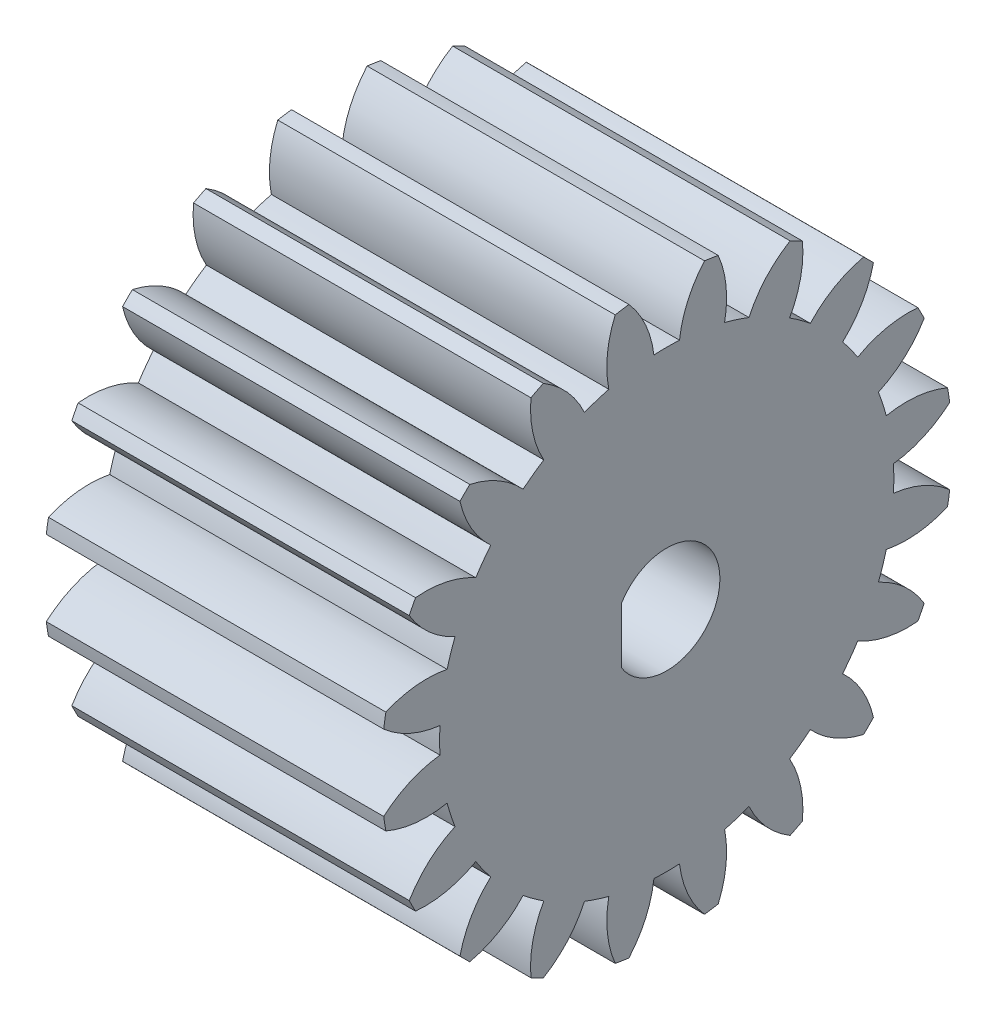
SolidWorks part; units mm, degrees
ref_plane "Plane1" through (0, 0, 0) normal (0, 0, 1) x (1, 0, 0)
ref_plane "Plane2" through (0, 0, 0) normal (0, 1, 0) x (1, 0, 0)
ref_plane "Plane3" through (0, 0, 0) normal (1, 0, 0) x (0, 0, -1)
other "Configuration Table"
sketch "HoldingSke" plane through (0, 0, 0) normal (0, 1, 0) x (1, 0, 0)
  line L0 (0, 0) -> (0.4698, -0.171)
  line L1 (-15, 0) -> (100, 0) construction
  line L2 (0, 0) -> (-2.1039, 2.3779)
  line L3 (0, 0) -> (-11.863, 4.5341)
  line L4 (0, 0) -> (8.1152, 2.9537)
  line L5 (0, 0) -> (-46.8476, -17.4728)
  line L6 (0, 0) -> (-21.553, -14.5419)
  line L7 (-2.1039, 2.3779) -> (8.6586, 51.2059)
  line L8 (-76.2, 54.61) -> (-75.9, 54.61)
  line L9 (-71.009, 38.7566) -> (-53.1078, 45.2721)
  line L10 (-76.2, 71.12) -> (104.1128, 71.12)
  line L11 (0, 0) -> (-26, 0)
  line L12 (-76.2, 101.6) -> (-76.133, 101.6)
  line L13 (24.9733, 27.94) -> (52.9518, 28.4284)
  line L14 (24.9733, 27.94) -> (24.9743, 27.94)
  line L15 (24.9733, 27.94) -> (100.4006, 29.5858)
  line L16 (-63.627, -2) -> (-12.827, -2)
  circle A0 centre (0, 0) radius 1
  circle A1 centre (0, 0) radius 17.499
  circle A2 centre (0, 0) radius 37.5
  circle A3 centre (0, 0) radius 1
  dimension "MHD" = 34.998
  dimension "Hub_dia" = 75
  dimension "Bore" = 2
  dimension "MBD" = 2
  dimension "Num_teeth" = 20
  dimension "Pitch" = 0.5
  dimension "Overall_len" = 50
  dimension "Show_teeth" = 20
  dimension "Thickness" = 26
  dimension "OAL" = 50.0001
  dimension "T_dim" = 0.3
  dimension "Ap" = 20
  dimension "H" = 19.05
  dimension "Pitch_radius" = 180.3128
  dimension "Width" = 26
  dimension "Backlash" = 0.067
  dimension "Addendum_fac" = 1
  dimension "Dedendum_fac" = 1.25
  dimension "Clearance_fac" = 0.25
  dimension "Dedendum_add" = 0.001
  dimension "Module" = 2
sketch "BasProSke" plane through (0, 0, 0) normal (0, 1, 0) x (1, 0, 0)
  line L0 (-10, 0) -> (60, 0) construction
  line L1 (0, 0) -> (0, 22)
  line L2 (0, 0) -> (26, 0)
  line L3 (26, 0) -> (26, 22)
  line L4 (26, 22) -> (0, 22)
  dimension "Thickness" = 26
  dimension "Diameter" = 44
revolve "Base-Revolve" add sketch "BasProSke" angle 360 about L0
sketch "TooCutSke" plane through (0, 0, 0) normal (1, 0, 0) x (0, 0, -1)
  line L1 (0, 0) -> (0, 107) construction
  line L2 (0, 0) -> (-1.6864, 19.9288) construction
  line L3 (0, 0) -> (-6.2409, 39.4033) construction
  line L4 (-1.6864, 19.9288) -> (-3.1204, 19.7016) construction
  arc A0 (0.9862, 17.4712) -> (-0.9862, 17.4712) centre (0, 0) ccw
  arc A1 (2.9329, 21.8293) -> (-2.9329, 21.8293) centre (0, 0) ccw
  circle A2 centre (0, 0) radius 20 construction
  circle A3 centre (0, 0) radius 18.7939 construction
  arc A4 (-0.9862, 17.4712) -> (-2.9329, 21.8293) centre (-8.9313, 16.536) ccw
  arc A5 (2.9329, 21.8293) -> (0.9862, 17.4712) centre (8.9313, 16.536) ccw
  dimension "Root_dia" = 34.998
  dimension "Overcut_dia" = 44.0508
  dimension "Pitch_dia" = 40
  dimension "Base_dia" = 37.5877
  dimension "Flank_rad" = 8
  dimension "Half_ang" = 9
  dimension "Half_CT" = 1.4519
extrude "ToothCut" cut sketch "TooCutSke" along normal through all
fillet "Breaks" [suppressed] radius 0.04
fillet "RootFillets" [suppressed] radius 0.501
pattern_circular "TeethCuts" count 20 every 18 about axis through (-10, 0, 0) along (1, 0, 0) of "ToothCut", "RootFillets", "Breaks"
sketch "HubNeaOneSke" plane through (0, 0, 0) normal (-1, 0, 0) x (0, 0, 1)
  circle A0 centre (0, 0) radius 17.499
  dimension "Diameter" = 34.998
extrude "HubNearOne" [suppressed] add sketch "HubNeaOneSke" along normal blind 24.0001
sketch "HubNeaBotSke" plane through (0, 0, 0) normal (-1, 0, 0) x (0, 0, 1)
  circle A0 centre (0, 0) radius 17.499
  dimension "Diameter" = 34.998
extrude "HubNearBoth" [suppressed] add sketch "HubNeaBotSke" along normal blind 12
ref_plane "FarPln" through (26, 0, 0) normal (1, 0, 0) x (0, 0, -1)
sketch "HubFarSke" plane through (26, 0, 0) normal (1, 0, 0) x (0, 0, -1)
  circle A0 centre (0, 0) radius 17.499
  dimension "Diameter" = 34.998
extrude "HubFar" [suppressed] add sketch "HubFarSke" along normal blind 12
sketch "BorSke" plane through (0, 0, 0) normal (1, 0, 0) x (0, 0, -1)
  line L0 (-3.5, -2.1354) -> (-3.5, 2.1354)
  arc A0 (-3.5, -2.1354) -> (-3.5, 2.1354) centre (0, 0) ccw
  dimension "D1" = 8.2
  dimension "D2" = 3.5
extrude "Bore" cut sketch "BorSke" along normal mid plane 100.0001
sketch "KeySke" plane through (0, 0, 0) normal (1, 0, 0) x (0, 0, -1)
  line L0 (-0.4, 0) -> (-0.4, 1.3)
  line L1 (-0.4, 1.3) -> (0.4, 1.3)
  line L2 (0.4, 1.3) -> (0.4, 0)
  line L3 (0, 0) -> (0, 34) construction
  line L4 (-0.4, 0) -> (0.4, 0)
  dimension "Offset" = 1.3
  dimension "Width" = 0.8
extrude "Keyway" [suppressed] cut sketch "KeySke" along normal mid plane 100.0001
pattern_circular "Keyway2" [suppressed] count 2 every 90 about axis through (-10, 0, 0) along (1, 0, 0)
equation "' \"Module@HoldingSke\" = 6.35"
equation "' \"Num_teeth@HoldingSke\" = 12"
equation "' \"Ap@HoldingSke\" =  20"
equation "' \"Ap@HoldingSke\" = 20"
equation "' \"Width@HoldingSke\" = 0.5 * 25.4"
equation "' \"Hub_dia@HoldingSke\"= 1 * 25.4"
equation "' \"Hub_dia@HoldingSke\" = 1 * 25.4"
equation "' \"Overall_len@HoldingSke\" = 1.0 * 25.4"
equation "' \"Bore@HoldingSke\" = 0.75 * 25.4"
equation "' \"T_dim@HoldingSke\" = 0.1 * 25.4"
equation "' \"Width@KeySke\" = 0.25 * 25.4"
equation "' \"Show_teeth@HoldingSke\" = 13"
equation "' \"Backlash@HoldingSke\" = 0.009 * 25.4"
equation "' \"Addendum_fac@HoldingSke\" = 1.0"
equation "' \"Dedendum_fac@HoldingSke\" = 1.25"
equation "' \"Dedendum_add@HoldingSke\" = 0.00005 * 25.4"
equation "' \"Clearance_fac@HoldingSke\" = 0.25"
equation "\"Pitch@HoldingSke\" = 1 / \"Module@HoldingSke\""
equation "\"Overcut_dia@TooCutSke\" = (\"Num_teeth@HoldingSke\" + 2 * \"Addendum_fac@HoldingSke\") / \"Pitch@HoldingSke\" + 0.002 * 25.4"
equation "\"Pitch_dia@TooCutSke\" = \"Num_teeth@HoldingSke\" / \"Pitch@HoldingSke\""
equation "\"Base_dia@TooCutSke\" = \"Num_teeth@HoldingSke\" / \"Pitch@HoldingSke\" * cos((\"Ap@HoldingSke\"  * 3.14159265 / 180))"
equation "\"Root_dia@TooCutSke\" = (\"Num_teeth@HoldingSke\" + 2) / \"Pitch@HoldingSke\" - 2 * (\"Addendum_fac@HoldingSke\" + \"Dedendum_fac@HoldingSke\") / \"Pitch@HoldingSke\" - \"Dedendum_add@HoldingSke\" * 2"
equation "\"Half_ang@TooCutSke\" = 180 / \"Num_teeth@HoldingSke\""
equation "\"Half_CT@TooCutSke\" = \"Num_teeth@HoldingSke\" / \"Pitch@HoldingSke\" * sin((3.14159265 / 2 / \"Num_teeth@HoldingSke\")) / 2 - 7 * \"Backlash@HoldingSke\" / 4"
equation "\"Flank_rad@TooCutSke\" = \"Num_teeth@HoldingSke\" / \"Pitch@HoldingSke\" / 5"
equation "\"Radius@RootFillets\" = \"Clearance_fac@HoldingSke\" / \"Pitch@HoldingSke\" + \"Dedendum_add@HoldingSke\""
equation "\"Break_rad@Breaks\" = 0.02 / \"Pitch@HoldingSke\""
equation "\"Thickness@HoldingSke\" = \"Width@HoldingSke\""
equation "\"OAL@HoldingSke\" = \"Thickness@HoldingSke\""
equation "\"MHD@HoldingSke\" = (\"Num_teeth@HoldingSke\" + 2) / \"Pitch@HoldingSke\" - 2 * (\"Addendum_fac@HoldingSke\" + \"Dedendum_fac@HoldingSke\")  / \"Pitch@HoldingSke\" - \"Dedendum_add@HoldingSke\" * 2"
equation "\"MBD@HoldingSke\" = (\"Num_teeth@HoldingSke\" + 2) / \"Pitch@HoldingSke\" - 2 * (\"Addendum_fac@HoldingSke\" + \"Dedendum_fac@HoldingSke\")  / \"Pitch@HoldingSke\" - \"Dedendum_add@HoldingSke\" * 2 - 0.002 * 25.4"
equation "\"MHD@HoldingSke\" = ((sgn( \"MHD@HoldingSke\" - \"Hub_dia@HoldingSke\" )-1)*( \"MHD@HoldingSke\" - \"Hub_dia@HoldingSke\" ))/-2+ \"Hub_dia@HoldingSke\""
equation "\"MBD@HoldingSke\" = ((sgn( \"MBD@HoldingSke\" - \"Bore@HoldingSke\" )-1)*( \"MBD@HoldingSke\" - \"Bore@HoldingSke\" ))/-2+ \"Bore@HoldingSke\""
equation "\"OAL@HoldingSke\" = ((sgn( \"OAL@HoldingSke\" - \"Overall_len@HoldingSke\" )+1)*( \"OAL@HoldingSke\" - \"Overall_len@HoldingSke\" ))/2 + \"Overall_len@HoldingSke\" + 0.000002 * 25.4"
equation "\"Num_teeth@TeethCuts\" = int( \"Show_teeth@HoldingSke\" ) + 1"
equation "\"Num_teeth@TeethCuts\" = ((sgn( \"Num_teeth@TeethCuts\" - \"Num_teeth@HoldingSke\" )-1)*( \"Num_teeth@TeethCuts\" - \"Num_teeth@HoldingSke\" ))/-2+ \"Num_teeth@HoldingSke\""
equation "\"Num_teeth@TeethCuts\" = ((sgn( \"Num_teeth@TeethCuts\" - 2.0)+1)*( \"Num_teeth@TeethCuts\" - 2.0))/2 +2.0"
equation "\"Angle@TeethCuts\" = 360.0 / \"Num_teeth@HoldingSke\""
equation "\"Diameter@BasProSke\" = (\"Num_teeth@HoldingSke\" + 2 * \"Addendum_fac@HoldingSke\") / \"Pitch@HoldingSke\""
equation "\"Thickness@BasProSke\"  = \"Thickness@HoldingSke\""
equation "' \"Fillet_rad@BasProSke\" =  \"Thickness@HoldingSke\" * 0.05"
equation "' \"Fillet_rad@BasProSke\" = \"Thickness@HoldingSke\" * 0.05"
equation "\"MHD@HoldingSke\" = ((sgn( \"MHD@HoldingSke\" - \"Root_dia@TooCutSke\" )-1)*( \"MHD@HoldingSke\" - \"Root_dia@TooCutSke\" ))/-2+ \"Root_dia@TooCutSke\""
equation "\"Diameter@HubNeaOneSke\" = \"MHD@HoldingSke\""
equation "\"Length@HubNearOne\" = \"OAL@HoldingSke\" - \"Thickness@BasProSke\""
equation "\"Diameter@HubNeaBotSke\" = \"MHD@HoldingSke\""
equation "\"Length@HubNearBoth\" = ( \"OAL@HoldingSke\" - \"Thickness@BasProSke\" ) / 2.0"
equation "\"Thickness@FarPln\" = \"Thickness@BasProSke\""
equation "\"Diameter@HubFarSke\" = \"MHD@HoldingSke\""
equation "\"Length@HubFar\" = ( \"OAL@HoldingSke\" - \"Thickness@BasProSke\" ) / 2.0"
equation "\"D1@Bore\" = \"OAL@HoldingSke\" * 2.0"
equation "\"D1@Keyway\" = \"OAL@HoldingSke\" * 2.0"
equation "\"Offset@KeySke\" = \"T_dim@HoldingSke\" + \"MBD@HoldingSke\" / 2.0"
